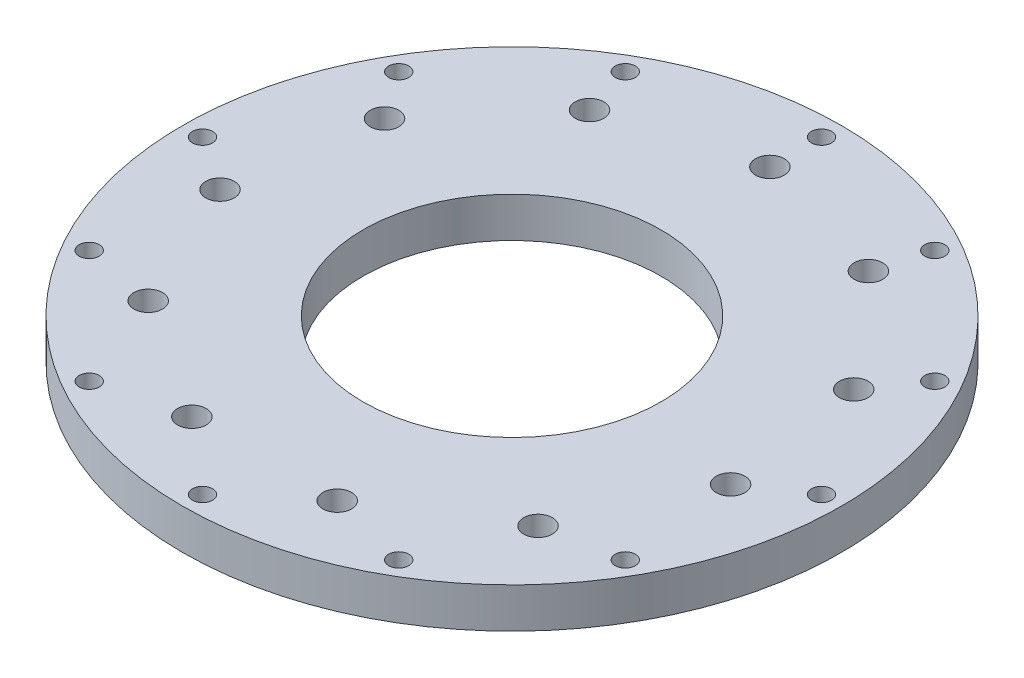
SolidWorks part; units mm, degrees
ref_plane "Front Plane" through (0, 0, 0) normal (0, 0, 1) x (1, 0, 0)
ref_plane "Top Plane" through (0, 0, 0) normal (0, 1, 0) x (1, 0, 0)
ref_plane "Right Plane" through (0, 0, 0) normal (1, 0, 0) x (0, 0, -1)
sketch "Sketch1" plane through (0, 0, 0) normal (0, 1, 0) x (1, 0, 0)
  circle A0 centre (0, 0) radius 57.5
  circle A1 centre (0, 0) radius 54 construction
  circle A2 centre (0, 54) radius 1.75
  circle A3 centre (27, 46.7654) radius 1.75
  circle A4 centre (46.7654, 27) radius 1.75
  circle A5 centre (54, 0) radius 1.75
  circle A6 centre (46.7654, -27) radius 1.75
  circle A7 centre (27, -46.7654) radius 1.75
  circle A8 centre (0, -54) radius 1.75
  circle A9 centre (-27, -46.7654) radius 1.75
  circle A10 centre (-46.7654, -27) radius 1.75
  circle A11 centre (-54, 0) radius 1.75
  circle A12 centre (-46.7654, 27) radius 1.75
  circle A13 centre (-27, 46.7654) radius 1.75
  circle A14 centre (0, 0) radius 26
  circle A15 centre (0, 0) radius 45 construction
  circle A16 centre (0, 45) radius 2.5
  circle A17 centre (24.3288, 37.8564) radius 2.5
  circle A18 centre (40.9334, 18.6937) radius 2.5
  circle A19 centre (44.542, -6.4042) radius 2.5
  circle A20 centre (34.0087, -29.4687) radius 2.5
  circle A21 centre (12.678, -43.1772) radius 2.5
  circle A22 centre (-12.678, -43.1772) radius 2.5
  circle A23 centre (-34.0087, -29.4687) radius 2.5
  circle A24 centre (-44.542, -6.4042) radius 2.5
  circle A25 centre (-40.9334, 18.6937) radius 2.5
  circle A26 centre (-24.3288, 37.8564) radius 2.5
  point P31 (0, 0)
  point P55 (0, 0)
  dimension "D1" = 115
  dimension "D2" = 108
  dimension "D3" = 3.5
  dimension "D4" = 52
  dimension "D5" = 90
  dimension "D6" = 5
extrude "Boss-Extrude1" add sketch "Sketch1" along normal blind 7
